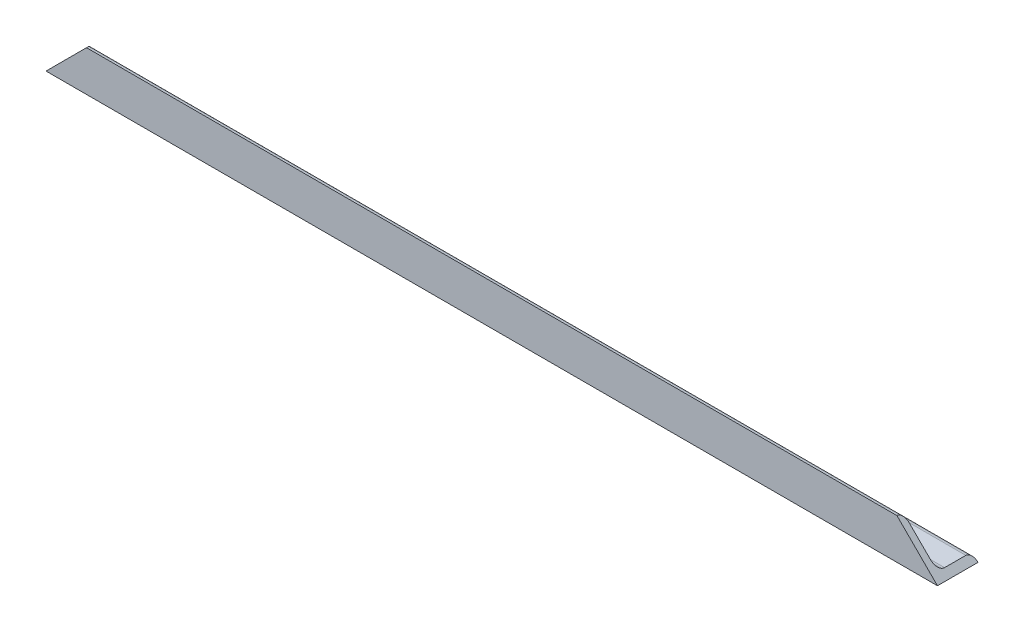
SolidWorks part; units mm, degrees
ref_plane "Front Plane" through (0, 0, 0) normal (0, 0, 1) x (1, 0, 0)
ref_plane "Top Plane" through (0, 0, 0) normal (0, 1, 0) x (1, 0, 0)
ref_plane "Right Plane" through (0, 0, 0) normal (1, 0, 0) x (0, 0, -1)
sketch "Sketch1" plane through (0, 0, 0) normal (0, 1, 0) x (1, 0, 0)
  line L0 (0, 0) -> (440, 0)
  dimension "D1" = 440
other "L angle (equal) 20X20X3(2)"
ref_plane "Plane1" through (0, 0, 0) normal (1, 0, 0) x (0, 0, -1)
sketch "Sketch16" plane through (0, 0, 0) normal (1, 0, 0) x (0, 0, -1)
  line L0 (0, 20) -> (0, 0)
  line L2 (3, 17) -> (3, 6.5)
  line L3 (6.5, 3) -> (17, 3)
  line L5 (20, 0) -> (0, 0)
  arc A0 (3, 17) -> (0, 20) centre (0, 17) ccw
  arc A1 (20, 0) -> (17, 3) centre (17, 0) ccw
  arc A2 (6.5, 3) -> (3, 6.5) centre (6.5, 6.5) cw
  point P8 (0, 10)
  point P9 (10, 0)
  point P10 (0, 0)
  dimension "Radius_2" = 3
  dimension "Radius_1" = 3.5
  dimension "V_leg" = 20
  dimension "H_leg" = 20
  dimension "thickness" = 3
sketch "Sketch14" plane through (0, 0, 0) normal (0, 0, 1) x (1, 0, 0)
  line L0 (440, 0) -> (440, 20)
  line L1 (0, 20) -> (0, 0)
  line L2 (20, 20) -> (0, 0)
  line L3 (420, 20) -> (440, 0)
  line L4 (0, 20) -> (0, 0)
  line L5 (0, 0) -> (440, 0)
  line L6 (440, 0) -> (440, 20)
  line L7 (440, 20) -> (0, 20)
  line L8 (0, 20) -> (0, 0) construction
  line L10 (440, 0) -> (440, 20) construction
  line L11 (440, 20) -> (420, 20)
  line L12 (20, 20) -> (0, 20)
  dimension "D2" = 20
  dimension "D3" = 20
  dimension "D1" = 0
extrude "Cut-Extrude1" cut sketch "Sketch14" against normal through all
